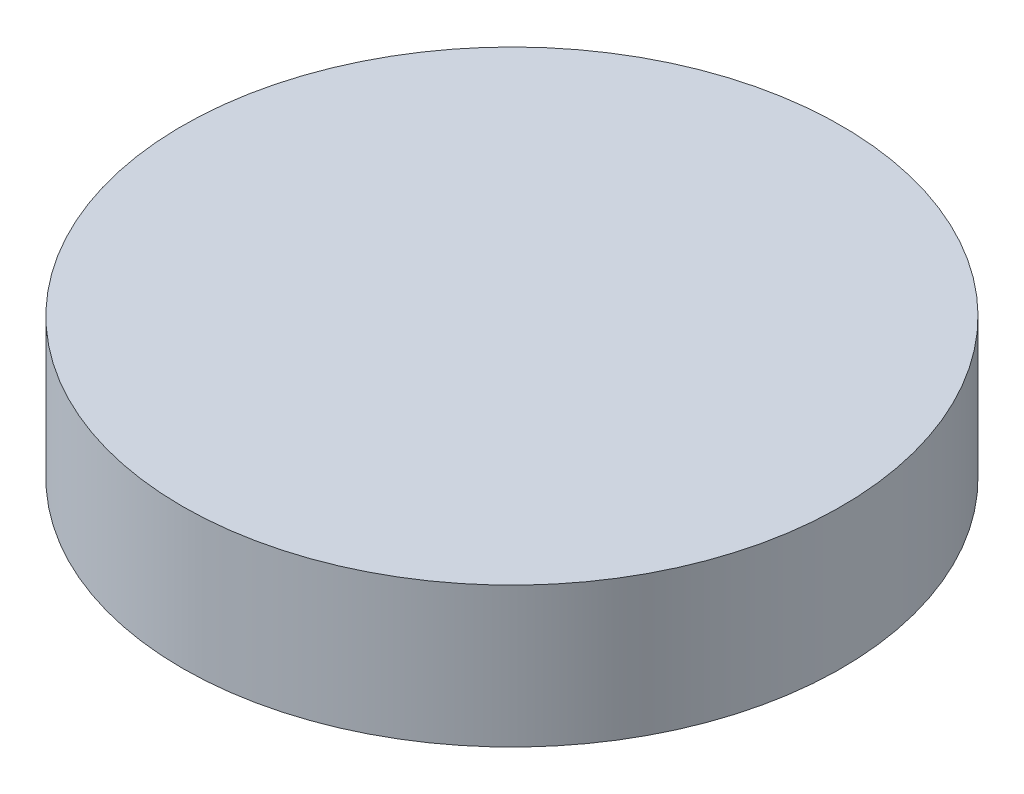
SolidWorks part; units mm, degrees
ref_plane "Front Plane" through (0, 0, 0) normal (0, 0, 1) x (1, 0, 0)
ref_plane "Top Plane" through (0, 0, 0) normal (0, 1, 0) x (1, 0, 0)
ref_plane "Right Plane" through (0, 0, 0) normal (1, 0, 0) x (0, 0, -1)
sketch "Sketch1" plane through (0, 0, 0) normal (0, 1, 0) x (1, 0, 0)
  circle A0 centre (0, 0) radius 5.969
extrude "Boss-Extrude1" add sketch "Sketch1" along normal blind 2.54
